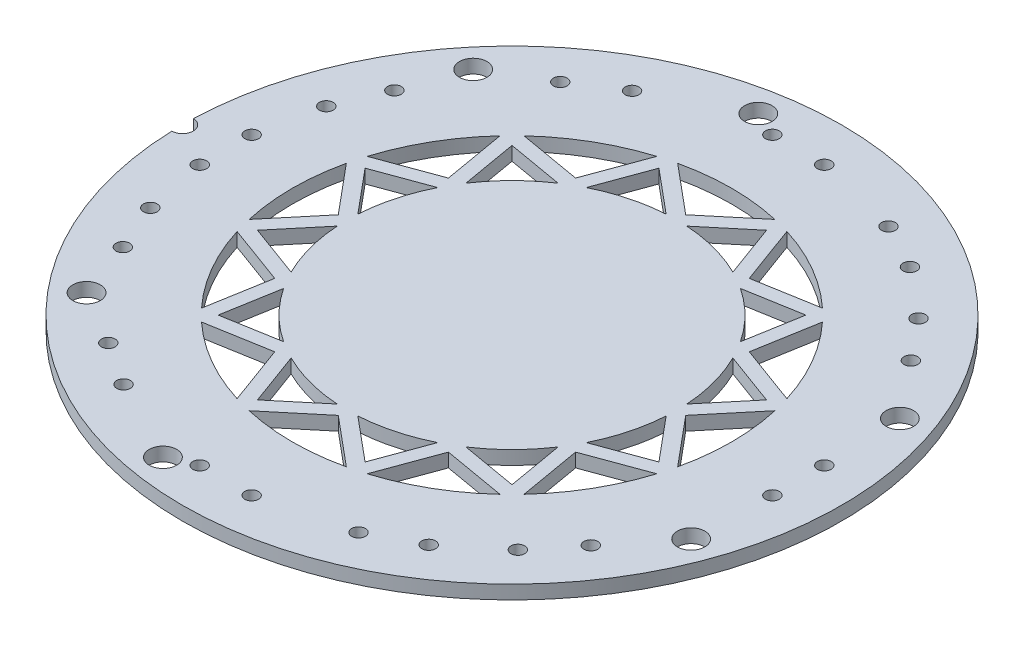
SolidWorks part; units mm, degrees
ref_plane "Front Plane" through (0, 0, 0) normal (0, 0, 1) x (1, 0, 0)
ref_plane "Top Plane" through (0, 0, 0) normal (0, 1, 0) x (1, 0, 0)
ref_plane "Right Plane" through (0, 0, 0) normal (1, 0, 0) x (0, 0, -1)
sketch "Sketch1" plane through (0, 0, 0) normal (0, 1, 0) x (1, 0, 0)
  line L0 (0, 0) -> (109.2336, 0) construction
  line L1 (0, 0) -> (-110.6657, 0) construction
  line L2 (27.076, -24.13) -> (65.5497, -24.13)
  line L3 (27.076, -24.13) -> (27.076, 24.13)
  line L4 (27.076, 24.13) -> (65.5497, 24.13)
  line L5 (65.5497, -24.13) -> (65.5497, 24.13)
  line L6 (27.076, -24.13) -> (65.5497, 24.13) construction
  line L7 (27.076, 24.13) -> (65.5497, -24.13) construction
  line L9 (-88.9, 35.56) -> (-38.1, 35.56)
  line L10 (-88.9, 35.56) -> (-88.9, -35.56)
  line L11 (-88.9, -35.56) -> (-38.1, -35.56)
  line L12 (-38.1, 35.56) -> (-38.1, -35.56)
  line L13 (-88.9, 35.56) -> (-38.1, -35.56) construction
  line L14 (-88.9, -35.56) -> (-38.1, 35.56) construction
  line L15 (98.6179, -32.5) -> (57.5497, -32.5)
  line L16 (98.6179, -32.5) -> (98.6179, 32.5)
  line L17 (98.6179, 32.5) -> (57.5497, 32.5)
  line L18 (57.5497, -32.5) -> (57.5497, 32.5)
  line L19 (98.6179, -32.5) -> (57.5497, 32.5) construction
  line L20 (98.6179, 32.5) -> (57.5497, -32.5) construction
  circle A0 centre (0, 0) radius 88.9
  circle A1 centre (0, 0) radius 69.85
  circle A2 centre (65.5497, 24.13) radius 3.175
  circle A3 centre (65.5497, -24.13) radius 3.175
  circle A4 centre (-53.6721, -44.7027) radius 3.175
  circle A5 centre (-11.8777, -68.8327) radius 3.175
  circle A6 centre (-11.8777, 68.8327) radius 3.175
  circle A7 centre (-53.6721, 44.7027) radius 3.175
  point P4 (46.3129, 0)
  point P12 (-63.5, 0)
  point P23 (0, 0)
  point P27 (78.0838, 0)
  dimension "D1" = 177.8
  dimension "D2" = 139.7
  dimension "D4" = 3
  dimension "D3" = 48.26
  dimension "D5" = 71.12
  dimension "D6" = 50.8
  dimension "D7" = 63.5
  dimension "D8" = 65
  dimension "D9" = 8
sketch "Sketch2" plane through (0, 0, 0) normal (0, 1, 0) x (1, 0, 0)
  circle A0 centre (0, 0) radius 88.9
extrude "Boss-Extrude1" add sketch "Sketch2" along normal blind 3.175
sketch "Sketch3" plane through (0, 3.175, 0) normal (0, 1, 0) x (1, 0, 0)
  line L4 (27.076, -24.13) -> (65.5497, -24.13)
  line L5 (65.5497, -24.13) -> (65.5497, 24.13)
  line L6 (65.5497, 24.13) -> (27.076, 24.13)
  line L7 (27.076, 24.13) -> (27.076, -24.13)
  line L8 (27.076, -24.13) -> (65.5497, -24.13)
  line L9 (65.5497, -24.13) -> (65.5497, 24.13)
  line L10 (65.5497, 24.13) -> (27.076, 24.13)
  line L11 (27.076, 24.13) -> (27.076, -24.13)
  line L12 (-38.1, 35.56) -> (-88.9, 35.56)
  line L13 (-38.1, -35.56) -> (-38.1, 35.56)
  line L14 (-88.9, -35.56) -> (-38.1, -35.56)
  line L15 (-88.9, 35.56) -> (-88.9, -35.56)
  line L16 (-38.1, 35.56) -> (-88.9, 35.56)
  line L17 (-38.1, -35.56) -> (-38.1, 35.56)
  line L18 (-88.9, -35.56) -> (-38.1, -35.56)
  line L19 (-88.9, 35.56) -> (-88.9, -35.56)
  circle A0 centre (0, 0) radius 76.2
  circle A1 centre (65.5497, -24.13) radius 3.175
  circle A2 centre (65.5497, -24.13) radius 3.175
  circle A3 centre (65.5497, 24.13) radius 3.175
  circle A4 centre (65.5497, 24.13) radius 3.175
  circle A5 centre (0, 0) radius 69.85
  circle A6 centre (0, 0) radius 69.85
  circle A7 centre (0, 0) radius 88.9
  circle A8 centre (0, 0) radius 88.9
  circle A9 centre (-53.6721, 44.7027) radius 3.175
  circle A10 centre (-53.6721, 44.7027) radius 3.175
  circle A11 centre (-11.8777, 68.8327) radius 3.175
  circle A12 centre (-11.8777, 68.8327) radius 3.175
  circle A13 centre (-11.8777, -68.8327) radius 3.175
  circle A14 centre (-11.8777, -68.8327) radius 3.175
  circle A15 centre (-53.6721, -44.7027) radius 3.175
  circle A16 centre (-53.6721, -44.7027) radius 3.175
  dimension "D1" = 0
  dimension "D2" = 0
  dimension "D3" = 0
  dimension "D4" = 0
  dimension "D5" = 0
  dimension "D6" = 0
  dimension "D7" = 0
  dimension "D8" = 0
  dimension "D9" = 0
  dimension "D10" = 0
extrude "Cut-Extrude1" cut sketch "Sketch3" against normal blind 3.175 contours A10 | A12 | A4 | A2 | A14 | A16
sketch "Sketch4" plane through (0, 3.175, 0) normal (0, 1, 0) x (1, 0, 0)
  line L0 (71.3917, 32.5) -> (71.3917, -32.5)
  line L4 (27.076, -24.13) -> (65.5497, -24.13)
  line L5 (65.5497, -24.13) -> (65.5497, 24.13)
  line L6 (65.5497, 24.13) -> (27.076, 24.13)
  line L7 (27.076, 24.13) -> (27.076, -24.13)
  line L8 (27.076, -24.13) -> (65.5497, -24.13)
  line L9 (65.5497, -24.13) -> (65.5497, 24.13)
  line L10 (65.5497, 24.13) -> (27.076, 24.13)
  line L11 (27.076, 24.13) -> (27.076, -24.13)
  line L12 (57.5497, -32.5) -> (98.6179, -32.5)
  line L13 (57.5497, 32.5) -> (57.5497, -32.5)
  line L14 (98.6179, 32.5) -> (57.5497, 32.5)
  line L15 (98.6179, -32.5) -> (98.6179, 32.5)
  line L16 (57.5497, -32.5) -> (98.6179, -32.5)
  line L17 (57.5497, 32.5) -> (57.5497, -32.5)
  line L18 (98.6179, 32.5) -> (57.5497, 32.5)
  line L19 (98.6179, -32.5) -> (98.6179, 32.5)
  line L20 (-38.1, 35.56) -> (-88.9, 35.56)
  line L21 (-38.1, -35.56) -> (-38.1, 35.56)
  line L22 (-88.9, -35.56) -> (-38.1, -35.56)
  line L23 (-88.9, 35.56) -> (-88.9, -35.56)
  line L24 (-38.1, 35.56) -> (-88.9, 35.56)
  line L25 (-38.1, -35.56) -> (-38.1, 35.56)
  line L26 (-88.9, -35.56) -> (-38.1, -35.56)
  line L27 (-88.9, 35.56) -> (-88.9, -35.56)
  circle A1 centre (65.5497, -24.13) radius 3.175
  circle A2 centre (65.5497, -24.13) radius 3.175
  circle A3 centre (65.5497, 24.13) radius 3.175
  circle A4 centre (65.5497, 24.13) radius 3.175
  circle A5 centre (0, 0) radius 69.85
  circle A6 centre (0, 0) radius 69.85
  circle A7 centre (0, 0) radius 88.9
  circle A8 centre (0, 0) radius 88.9
  circle A9 centre (-53.6721, 44.7027) radius 3.175
  circle A10 centre (-53.6721, 44.7027) radius 3.175
  circle A11 centre (-11.8777, 68.8327) radius 3.175
  circle A12 centre (-11.8777, 68.8327) radius 3.175
  circle A13 centre (-11.8777, -68.8327) radius 3.175
  circle A14 centre (-11.8777, -68.8327) radius 3.175
  circle A15 centre (-53.6721, -44.7027) radius 3.175
  circle A16 centre (-53.6721, -44.7027) radius 3.175
  dimension "D12" = 5.842
  dimension "D1" = 0
  dimension "D2" = 0
  dimension "D3" = 0
  dimension "D4" = 0
  dimension "D5" = 0
  dimension "D6" = 0
  dimension "D7" = 0
  dimension "D8" = 0
  dimension "D9" = 0
  dimension "D10" = 0
  dimension "D11" = 0
sketch "Sketch6" plane through (0, 3.175, 0) normal (0, 1, 0) x (1, 0, 0)
  circle A0 centre (0, 0) radius 76.2
  circle A1 centre (0, 0) radius 88.9
  dimension "D1" = 152.4
extrude "Cut-Extrude2" cut sketch "Sketch6" against normal through all
sketch "Sketch7" plane through (0, 3.175, 0) normal (0, 1, 0) x (1, 0, 0)
  line L0 (0, 0) -> (-124.1416, 0) construction
  line L1 (-76.2, 13.4) -> (0, 0)
  line L2 (-86.4, -13.4) -> (-76.2, -13.4)
  line L3 (-86.4, -13.4) -> (-86.4, 13.4)
  line L4 (-86.4, 13.4) -> (-76.2, 13.4)
  line L5 (-76.2, -13.4) -> (-76.2, 13.4)
  line L6 (-86.4, -13.4) -> (-76.2, 13.4) construction
  line L7 (-86.4, 13.4) -> (-76.2, -13.4) construction
  line L8 (-66.2, -6) -> (-76.2, -6)
  line L9 (-66.2, -6) -> (-66.2, 6)
  line L10 (-66.2, 6) -> (-76.2, 6)
  line L11 (-76.2, -6) -> (-76.2, 6)
  line L12 (-66.2, -6) -> (-76.2, 6) construction
  line L13 (-66.2, 6) -> (-76.2, -6) construction
  line L14 (-76.2, -13.4) -> (0, 0)
  circle A0 centre (-66.2, 6) radius 1.5875
  circle A1 centre (-66.2, -6) radius 1.5875
  point P3 (-81.3, 0)
  point P8 (-71.2, 0)
  dimension "D4" = 3.175
  dimension "D1" = 10.2
  dimension "D2" = 26.8
  dimension "D3" = 76.2
  dimension "D5" = 12
  dimension "D6" = 10
extrude "Cut-Extrude3" cut sketch "Sketch7" against normal through all and the other way through all
sketch "Sketch8" plane through (0, 3.175, 0) normal (0, 1, 0) x (1, 0, 0)
  line L0 (0, 0) -> (-86.6799, 0)
  circle A0 centre (-76.2, 0) radius 2.5
  circle A1 centre (0, 0) radius 76.2 construction
  dimension "D1" = 5
extrude "Cut-Extrude4" cut sketch "Sketch8" against normal through all contours A0
pattern_circular "CirPattern1" count 2 every 23 about axis through (0, 0, 0) along (0, 1, 0) of "Cut-Extrude3"
pattern_circular "CirPattern2" count 2 every 57 about axis through (0, 0, 0) along (0, 1, 0) of "Cut-Extrude3"
sketch "Sketch9" plane through (0, 3.175, 0) normal (0, 1, 0) x (1, 0, 0)
  line L0 (0, 0) -> (0, -76.2) construction
  line L2 (0, -66.2) -> (25.4, -66.2)
  line L3 (0, -66.2) -> (0, -76.2)
  line L4 (0, -76.2) -> (25.4, -76.2)
  line L5 (25.4, -66.2) -> (25.4, -76.2)
  arc A0 (-76.159, -2.4997) -> (-76.159, 2.4997) centre (0, 0) ccw construction
  circle A2 centre (25.4, -66.2) radius 1.5875
  circle A3 centre (13.4, -66.2) radius 1.5875
  dimension "D3" = 3.175
  dimension "D4" = 3.175
  dimension "D1" = 10
  dimension "D2" = 25.4
  dimension "D5" = 12
extrude "Cut-Extrude5" [suppressed] cut sketch "Sketch9" against normal blind 10
pattern_circular "CirPattern3" count 2 every 90 about axis through (0, 0, 0) along (0, 1, 0) of "Cut-Extrude3"
pattern_circular "CirPattern4" count 2 every 180 about axis through (0, 0, 0) along (0, 1, 0) of "Cut-Extrude3"
pattern_circular "CirPattern6" count 2 every 141 about axis through (0, 0, 0) along (0, 1, 0) of "Cut-Extrude3"
pattern_circular "CirPattern7" count 2 every 118 about axis through (0, 0, 0) along (0, 1, 0) of "Cut-Extrude3"
mirror "Mirror3" about plane through (0, 0, 0) normal (0, 0, 1) of "CirPattern1", "CirPattern2", "CirPattern3", "CirPattern6", "CirPattern7"
sketch "Sketch10" plane through (0, 3.175, 0) normal (0, 1, 0) x (1, 0, 0)
  line L0 (0, 0) -> (-50.8, 0)
  line L1 (0, 0) -> (-43.9941, 25.4)
  line L2 (-50.8, 1.5875) -> (0, 1.5875)
  line L3 (-50.8, 1.5875) -> (-50.8, -1.5875)
  line L4 (0, 1.5875) -> (0, -1.5875)
  line L5 (-50.8, -1.5875) -> (0, -1.5875)
  line L6 (-50.8, 1.5875) -> (0, -1.5875) construction
  line L7 (0, 1.5875) -> (-50.8, -1.5875) construction
  line L8 (0, 0) -> (-49.069, 13.148)
  line L9 (-49.069, 13.148) -> (-38.1, 0)
  line L10 (-49.069, 13.148) -> (-32.9956, 19.05)
  circle A0 centre (0, 0) radius 38.1
  circle A1 centre (0, 0) radius 50.8
  point P7 (-25.4, 0)
  dimension "D1" = 30
  dimension "D2" = 3.175
  dimension "D3" = 15
sketch "Sketch11" plane through (0, 3.175, 0) normal (0, 1, 0) x (1, 0, 0)
  circle A0 centre (0, 0) radius 50.8
  circle A1 centre (0, 0) radius 38.1
extrude "Cut-Extrude6" cut sketch "Sketch11" against normal through all contours A0 A1
sketch "Sketch12" plane through (0, 3.175, 0) normal (0, 1, 0) x (1, 0, 0)
  line L0 (-49.069, 13.148) -> (-32.9956, 19.05) construction
  line L1 (-49.069, 13.148) -> (-38.1, 0) construction
  line L2 (-35.921, 35.921) -> (-32.9956, 19.05)
  line L3 (-35.921, 35.921) -> (-19.05, 32.9956)
  line L4 (0, 1.5875) -> (-50.8, 1.5875)
  line L5 (0, -1.5875) -> (0, 1.5875)
  line L6 (-50.8, -1.5875) -> (0, -1.5875)
  line L7 (-50.8, 1.5875) -> (-50.8, -1.5875)
  line L10 (-50.8, -1.5875) -> (-50.7752, -1.5875)
  line L11 (-50.8, 1.5875) -> (-50.8, -1.5875)
  line L13 (-49.069, 13.148) -> (-32.9956, 19.05)
  line L14 (-49.069, 13.148) -> (-38.1, 0)
  line L15 (-13.148, 49.069) -> (-19.05, 32.9956)
  line L16 (-13.148, 49.069) -> (0, 38.1)
  line L18 (-50.7752, 1.5875) -> (-50.8, 1.5875)
  line L19 (13.148, 49.069) -> (0, 38.1)
  line L20 (-38.0669, 1.5875) -> (-39.4244, 1.5875)
  line L23 (13.148, 49.069) -> (19.05, 32.9956)
  line L24 (35.921, 35.921) -> (19.05, 32.9956)
  line L25 (35.921, 35.921) -> (32.9956, 19.05)
  line L26 (49.069, 13.148) -> (32.9956, 19.05)
  line L27 (49.069, 13.148) -> (38.1, 0)
  line L28 (49.069, -13.148) -> (38.1, 0)
  line L29 (49.069, -13.148) -> (32.9956, -19.05)
  line L30 (35.921, -35.921) -> (32.9956, -19.05)
  line L31 (35.921, -35.921) -> (19.05, -32.9956)
  line L32 (13.148, -49.069) -> (19.05, -32.9956)
  line L33 (13.148, -49.069) -> (0, -38.1)
  line L34 (-13.148, -49.069) -> (0, -38.1)
  line L35 (-13.148, -49.069) -> (-19.05, -32.9956)
  line L36 (-35.921, -35.921) -> (-19.05, -32.9956)
  line L37 (-35.921, -35.921) -> (-32.9956, -19.05)
  line L38 (-49.069, -13.148) -> (-32.9956, -19.05)
  line L39 (-49.069, -13.148) -> (-38.1, 0)
  circle A1 centre (0, 0) radius 50.8
  circle A2 centre (0, 0) radius 50.8
  circle A3 centre (0, 0) radius 38.1
  circle A4 centre (0, 0) radius 38.1
  point P58 (0, 0)
  dimension "D1" = 0
  dimension "D2" = 0
  dimension "D3" = 0
  dimension "D4" = 12
extrude "Extrude-Thin2" add sketch "Sketch12" against normal blind 3.175 thin contours L14 L39 L38 L37 L36 L35 L34 L33 L32 L31 L30 L29 L28 L27 L26 L25 L24 L23 L19 L16 L15 L3 L2 L13
equation "\"ㄅ\"=0.8"
